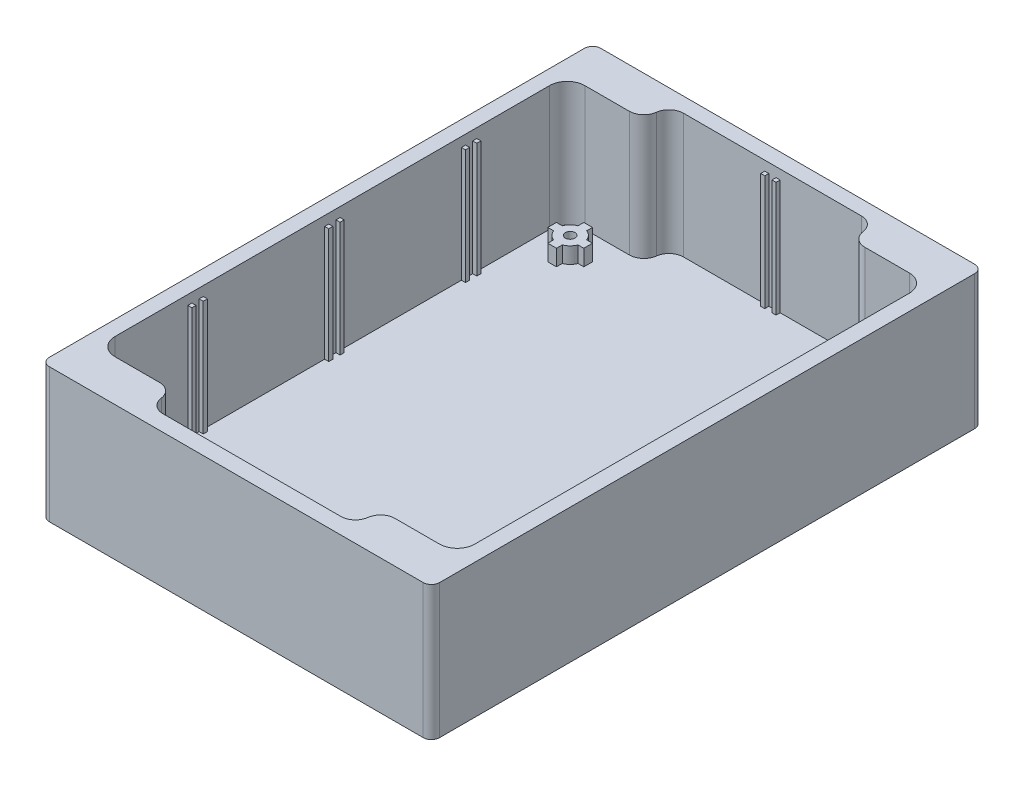
SolidWorks part; units mm, degrees
ref_plane "Front Plane" through (0, 0, 0) normal (0, 0, 1) x (1, 0, 0)
ref_plane "Top Plane" through (0, 0, 0) normal (0, 1, 0) x (1, 0, 0)
ref_plane "Right Plane" through (0, 0, 0) normal (1, 0, 0) x (0, 0, -1)
sketch "Sketch3" plane through (0, 0, 0) normal (0, 1, 0) x (1, 0, 0)
  line L0 (-59.6247, 84.5622) -> (59.893, -84.9427) construction
  line L1 (58.0969, -85.6866) -> (-57.8287, -85.6866)
  line L2 (60.6369, -83.1466) -> (60.6369, 82.7662)
  line L3 (58.0969, 85.3062) -> (-57.8287, 85.3062)
  line L4 (-60.3687, -83.1466) -> (-60.3687, 82.7662)
  line L5 (-59.6247, -84.9427) -> (59.5562, 84.8451) construction
  arc A0 (-57.8287, -85.6866) -> (-60.3687, -83.1466) centre (-57.8287, -83.1466) cw
  arc A1 (58.0969, -85.6866) -> (60.6369, -83.1466) centre (58.0969, -83.1466) ccw
  arc A2 (60.6369, 82.7662) -> (58.0969, 85.3062) centre (58.0969, 82.7662) ccw
  arc A3 (-57.8287, 85.3062) -> (-60.3687, 82.7662) centre (-57.8287, 82.7662) ccw
  point P4 (0, 0)
  point P71 (0, 80.899)
  dimension "D3" = 2.54
  dimension "D1" = 170.9928
  dimension "D2" = 121.0056
extrude "Boss-Extrude1" add sketch "Sketch3" along normal blind 41.656
sketch "Sketch6" plane through (0, 41.656, 0) normal (0, 1, 0) x (1, 0, 0)
  line L0 (0.1341, -85.6866) -> (0.1341, 85.3062) construction
  line L1 (-57.8287, -85.6866) -> (58.0969, -85.6866) construction
  line L2 (58.0969, 85.3062) -> (-57.8287, 85.3062) construction
  line L3 (60.6369, -0.1902) -> (-60.3687, -0.1902) construction
  line L4 (60.6369, -83.1466) -> (60.6369, 82.7662) construction
  line L5 (-60.3687, 82.7662) -> (-60.3687, -83.1466) construction
  line L6 (-55.7713, -0.1902) -> (-55.7713, 67.3734)
  line L7 (-50.3099, 72.8348) -> (-36.5179, 72.8348)
  line L8 (-27.5788, 80.7088) -> (0.1341, 80.7088)
  line L9 (-55.7713, -0.1902) -> (0.1341, -0.1902)
  line L10 (0.1341, -0.1902) -> (0.1341, 80.7088)
  arc A0 (-55.7713, 67.3734) -> (-50.3099, 72.8348) centre (-50.3099, 67.3734) cw
  arc A1 (-36.5179, 72.8348) -> (-32.0484, 76.7718) centre (-36.5179, 77.3403) ccw
  arc A2 (-32.0484, 76.7718) -> (-27.5788, 80.7088) centre (-27.5788, 76.2032) cw
  point P21 (-43.4139, 72.8348)
  dimension "D1" = 4.5974
  dimension "D2" = 4.5974
  dimension "D3" = 73.025
extrude "Cut-Extrude1" cut sketch "Sketch6" against normal blind 38.608
sketch "Sketch7" plane through (0, 3.048, 0) normal (0, 1, 0) x (1, 0, 0)
  line L1 (-55.7713, -0.1902) -> (0.1341, -0.1902) construction
  line L2 (-50.3787, 63.9448) -> (-40.2304, 63.9448) construction
  line L3 (0, 0) -> (0, 106.8773) construction
  line L4 (-45.974, 70.0943) -> (-45.974, 58.35) construction
  line L5 (-47.3177, 67.7129) -> (-47.3177, 69.5297)
  line L6 (-47.3177, 69.5297) -> (-44.6303, 69.5297)
  line L7 (-44.6303, 69.5297) -> (-44.6303, 67.7129)
  line L9 (-42.2059, 65.2884) -> (-40.3891, 65.2884)
  line L10 (-40.3891, 65.2884) -> (-40.3891, 62.6011)
  line L11 (-40.3891, 62.6011) -> (-42.2059, 62.6011)
  line L12 (-44.6303, 60.1767) -> (-44.6303, 58.3599)
  line L13 (-44.6303, 58.3599) -> (-47.3177, 58.3599)
  line L14 (-47.3177, 58.3599) -> (-47.3177, 60.1767)
  line L15 (-49.7421, 62.6011) -> (-51.5589, 62.6011)
  line L16 (-51.5589, 62.6011) -> (-51.5589, 65.2884)
  line L17 (-51.5589, 65.2884) -> (-49.7421, 65.2884)
  circle A0 centre (-45.974, 63.9448) radius 1.5
  arc A1 (-49.7421, 65.2884) -> (-47.3177, 67.7129) centre (-45.974, 63.9448) cw
  arc A2 (-44.6303, 67.7129) -> (-42.2059, 65.2884) centre (-45.974, 63.9448) cw
  arc A3 (-42.2059, 62.6011) -> (-44.6303, 60.1767) centre (-45.974, 63.9448) cw
  arc A4 (-47.3177, 60.1767) -> (-49.7421, 62.6011) centre (-45.974, 63.9448) cw
  point P14 (-45.974, 69.5297)
  point P41 (-45.466, 65.6974)
  dimension "D1" = 3
  dimension "D4" = 4.0005
  dimension "D2" = 64.135
  dimension "D3" = 45.974
extrude "Boss-Extrude2" add sketch "Sketch7" along normal blind 5
mirror "Mirror1" about plane through (0, 0, 0) normal (1, 0, 0) of "Cut-Extrude1", "Boss-Extrude2"
mirror "Mirror2" about plane through (0, 0, 0) normal (0, 0, 1) of "Mirror1", "Cut-Extrude1", "Boss-Extrude2"
sketch "Sketch9" plane through (0, 41.656, 0) normal (0, 1, 0) x (1, 0, 0)
  line L0 (27.5788, 80.7088) -> (-27.5788, 80.7088) construction
  line L1 (-2.3876, 80.7088) -> (-1.1176, 80.7088)
  line L2 (-2.3876, 80.7088) -> (-2.3876, 79.4388)
  line L3 (-2.3876, 79.4388) -> (-1.1176, 79.4388)
  line L4 (-1.1176, 80.7088) -> (-1.1176, 79.4388)
  line L6 (1.1176, 80.7088) -> (2.3876, 80.7088)
  line L7 (1.1176, 80.7088) -> (1.1176, 79.4388)
  line L8 (1.1176, 79.4388) -> (2.3876, 79.4388)
  line L9 (2.3876, 80.7088) -> (2.3876, 79.4388)
  line L10 (0, 0) -> (0, 86.1037) construction
  point P10 (1.1176, 80.0738)
  dimension "D1" = 1.27
  dimension "D2" = 1.27
  dimension "D3" = 2.2352
  dimension "D4" = 1.27
  dimension "D5" = 1.27
  dimension "D6" = 1.1176
extrude "Boss-Extrude3" add sketch "Sketch9" against normal up to surface (35.6616 mm away) from offset 2.9464 up to face at (-45.974, 3.048, -62.4448) offset against normal yes
mirror "Mirror3" about plane through (0, 0, 0) normal (0, 0, 1) of "Boss-Extrude3"
sketch "Sketch10" plane through (0, 41.656, 0) normal (0, 1, 0) x (1, 0, 0)
  line L0 (55.7713, 67.3734) -> (55.7713, -67.3734) construction
  line L1 (55.7713, -1.1176) -> (54.5013, -1.1176)
  line L2 (55.7713, -1.1176) -> (55.7713, -2.3876)
  line L3 (55.7713, -2.3876) -> (54.5013, -2.3876)
  line L4 (54.5013, -1.1176) -> (54.5013, -2.3876)
  line L5 (0, 0) -> (71.3841, 0) construction
  line L6 (55.7713, 2.3876) -> (54.5013, 2.3876)
  line L7 (55.7713, 2.3876) -> (55.7713, 1.1176)
  line L8 (55.7713, 1.1176) -> (54.5013, 1.1176)
  line L9 (54.5013, 2.3876) -> (54.5013, 1.1176)
  line L10 (55.7713, 41.3004) -> (54.5013, 41.3004)
  line L11 (55.7713, 41.3004) -> (55.7713, 40.0304)
  line L12 (55.7713, 40.0304) -> (54.5013, 40.0304)
  line L13 (54.5013, 41.3004) -> (54.5013, 40.0304)
  line L14 (0, 42.418) -> (67.2666, 42.418) construction
  line L15 (55.7713, 44.8056) -> (54.5013, 44.8056)
  line L16 (55.7713, 44.8056) -> (55.7713, 43.5356)
  line L17 (55.7713, 43.5356) -> (54.5013, 43.5356)
  line L18 (54.5013, 44.8056) -> (54.5013, 43.5356)
  line L19 (55.7713, 67.3734) -> (55.7713, -67.3734) construction
  line L20 (55.7713, -43.5356) -> (54.5013, -43.5356)
  line L21 (55.7713, -43.5356) -> (55.7713, -44.8056)
  line L22 (55.7713, -44.8056) -> (54.5013, -44.8056)
  line L23 (54.5013, -43.5356) -> (54.5013, -44.8056)
  line L24 (0, -42.418) -> (31.9738, -42.418) construction
  line L25 (55.7713, -40.0304) -> (54.5013, -40.0304)
  line L26 (55.7713, -40.0304) -> (55.7713, -41.3004)
  line L27 (55.7713, -41.3004) -> (54.5013, -41.3004)
  line L28 (54.5013, -40.0304) -> (54.5013, -41.3004)
  line L29 (0, 42.418) -> (0, -49.9507) construction
  point P14 (55.1363, 1.1176)
  point P25 (55.1363, 43.5356)
  point P41 (55.1363, -41.3004)
  dimension "D1" = 1.27
  dimension "D2" = 1.27
  dimension "D3" = 1.27
  dimension "D4" = 1.27
  dimension "D5" = 2.2352
  dimension "D6" = 1.1176
  dimension "D7" = 1.27
  dimension "D8" = 1.27
  dimension "D9" = 1.27
  dimension "D10" = 1.27
  dimension "D11" = 2.2352
  dimension "D12" = 1.1176
  dimension "D13" = 42.418
  dimension "D14" = 1.27
  dimension "D15" = 1.27
  dimension "D16" = 1.27
  dimension "D17" = 1.27
  dimension "D18" = 2.2352
  dimension "D19" = 1.1176
  dimension "D20" = 42.418
extrude "Boss-Extrude4" add sketch "Sketch10" against normal up to surface (35.6616 mm away) from offset 2.9464 up to face at (-45.974, 3.048, -62.4448) offset against normal yes
mirror "Mirror4" about plane through (0, 0, 0) normal (1, 0, 0) of "Boss-Extrude4"
